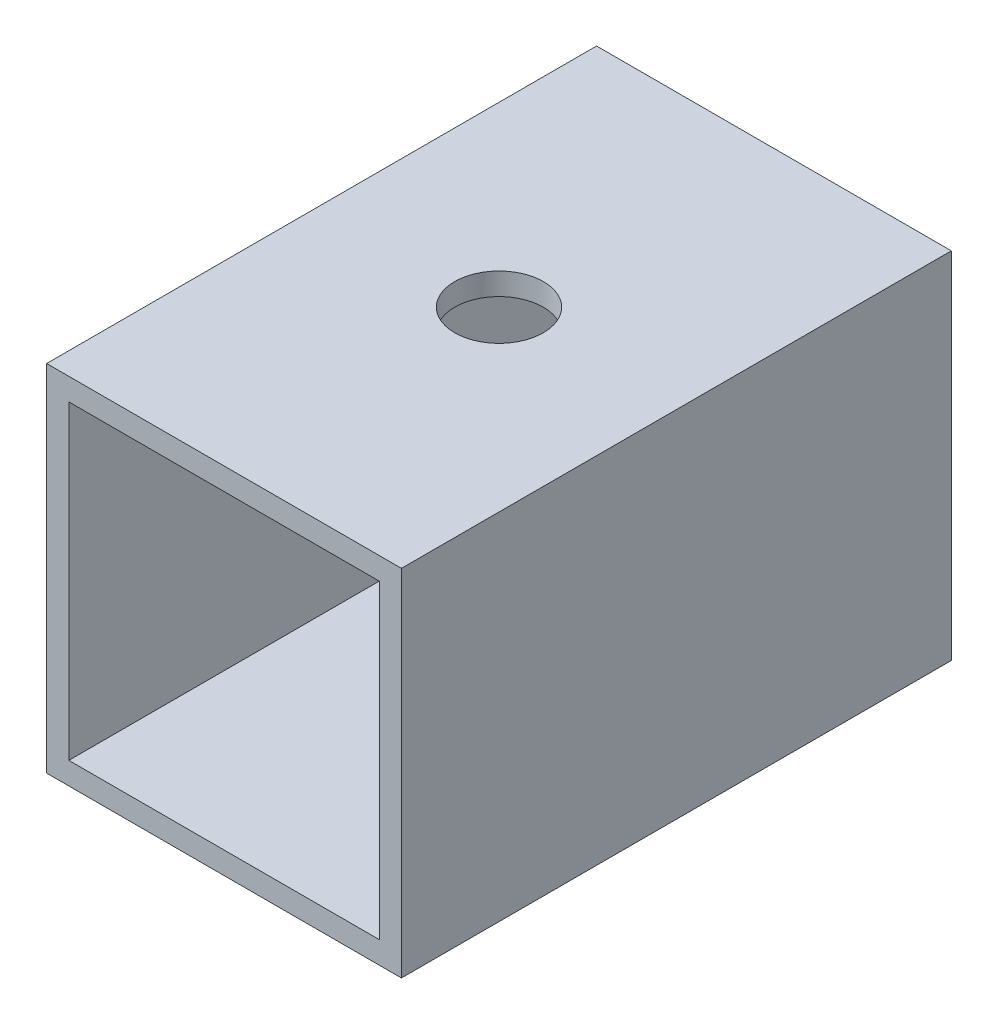
SolidWorks part; units mm, degrees
ref_plane "Front Plane" through (0, 0, 0) normal (0, 0, 1) x (1, 0, 0)
ref_plane "Top Plane" through (0, 0, 0) normal (0, 1, 0) x (1, 0, 0)
ref_plane "Right Plane" through (0, 0, 0) normal (1, 0, 0) x (0, 0, -1)
sketch "Sketch1" plane through (0, 0, 0) normal (0, 0, 1) x (1, 0, 0)
  line L1 (-12.7, 12.7) -> (12.7, 12.7)
  line L2 (-12.7, 12.7) -> (-12.7, -12.7)
  line L3 (-12.7, -12.7) -> (12.7, -12.7)
  line L4 (12.7, 12.7) -> (12.7, -12.7)
  line L5 (-12.7, 12.7) -> (12.7, -12.7) construction
  line L6 (-12.7, -12.7) -> (12.7, 12.7) construction
  line L7 (-11.1125, 11.1125) -> (11.1125, 11.1125)
  line L8 (-11.1125, 11.1125) -> (-11.1125, -11.1125)
  line L9 (-11.1125, -11.1125) -> (11.1125, -11.1125)
  line L10 (11.1125, 11.1125) -> (11.1125, -11.1125)
  line L11 (-11.1125, 11.1125) -> (11.1125, -11.1125) construction
  line L12 (-11.1125, -11.1125) -> (11.1125, 11.1125) construction
  point P0 (0, 0)
  point P6 (0, 0)
  dimension "D1" = 25.4
  dimension "D2" = 25.4
  dimension "D3" = 22.225
  dimension "D4" = 22.225
extrude "Boss-Extrude1" add sketch "Sketch1" along normal blind 39.37
sketch "Sketch2" plane through (0, 12.7, 0) normal (0, 1, 0) x (1, 0, 0)
  line L0 (-12.7, -39.37) -> (-12.7, 0) construction
  line L1 (12.7, -39.37) -> (-12.7, -39.37) construction
  circle A0 centre (0, -19.685) radius 3.175
  dimension "D1" = 6.35
  dimension "D2" = 12.7
  dimension "D3" = 19.685
extrude "Cut-Extrude1" cut sketch "Sketch2" against normal blind 25.4
